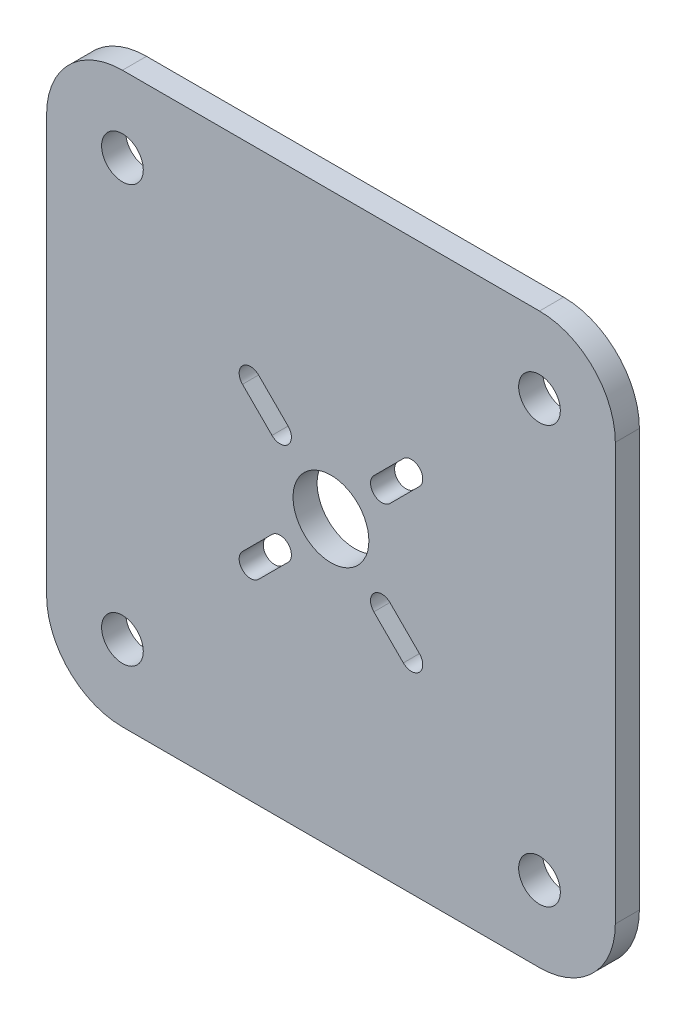
SolidWorks part; units mm, degrees
ref_plane "Front Plane" through (0, 0, 0) normal (0, 0, 1) x (1, 0, 0)
ref_plane "Top Plane" through (0, 0, 0) normal (0, 1, 0) x (1, 0, 0)
ref_plane "Right Plane" through (0, 0, 0) normal (1, 0, 0) x (0, 0, -1)
sketch "Sketch1" plane through (0, 0, 151.125) normal (0, 0, 1) x (1, 0, 0)
  line L1 (-37.5, 241.9) -> (37.5, 241.9)
  line L2 (-37.5, 241.9) -> (-37.5, 316.9)
  line L3 (-37.5, 316.9) -> (37.5, 316.9)
  line L4 (37.5, 241.9) -> (37.5, 316.9)
  line L5 (-37.5, 241.9) -> (37.5, 316.9) construction
  line L6 (-37.5, 316.9) -> (37.5, 241.9) construction
  circle A0 centre (0, 279.4) radius 3.25 construction
  circle A1 centre (-27.5, 251.9) radius 2.75 construction
  circle A2 centre (27.5, 251.9) radius 2.75 construction
  circle A3 centre (27.5, 306.9) radius 2.75 construction
  circle A4 centre (-27.5, 306.9) radius 2.75 construction
  circle A5 centre (0, 279.4) radius 3.25 construction
  circle A6 centre (-27.5, 251.9) radius 2.75
  circle A7 centre (27.5, 251.9) radius 2.75
  circle A8 centre (27.5, 306.9) radius 2.75
  circle A9 centre (-27.5, 306.9) radius 2.75
  circle A10 centre (0, 279.4) radius 5
  dimension "D1" = 10
  dimension "D2" = 75
extrude "Boss-Extrude1" add sketch "Sketch1" along normal blind 3.175
sketch "Sketch2" plane through (0, 0, 154.3) normal (0, 0, 1) x (1, 0, 0)
  line L0 (6.7175, 286.1175) -> (10.6066, 290.0066) construction
  line L1 (-6.7175, 272.6825) -> (6.7175, 272.6825) construction
  line L2 (-6.7175, 272.6825) -> (-6.7175, 286.1175) construction
  line L3 (-6.7175, 286.1175) -> (6.7175, 286.1175) construction
  line L4 (6.7175, 272.6825) -> (6.7175, 286.1175) construction
  line L5 (-6.7175, 272.6825) -> (6.7175, 286.1175) construction
  line L6 (-6.7175, 286.1175) -> (6.7175, 272.6825) construction
  line L7 (5.6569, 287.1782) -> (9.5459, 291.0673)
  line L8 (7.7782, 285.0569) -> (11.6673, 288.9459)
  line L9 (6.7175, 272.6825) -> (10.6066, 268.7934) construction
  line L10 (7.7782, 273.7431) -> (11.6673, 269.8541)
  line L11 (5.6569, 271.6218) -> (9.5459, 267.7327)
  line L12 (-6.7175, 272.6825) -> (-10.6066, 268.7934) construction
  line L13 (-5.6569, 271.6218) -> (-9.5459, 267.7327)
  line L14 (-7.7782, 273.7431) -> (-11.6673, 269.8541)
  line L15 (-6.7175, 286.1175) -> (-10.6066, 290.0066) construction
  line L16 (-7.7782, 285.0569) -> (-11.6673, 288.9459)
  line L17 (-5.6569, 287.1782) -> (-9.5459, 291.0673)
  circle A0 centre (0, 279.4) radius 5 construction
  circle A1 centre (0, 279.4) radius 5 construction
  circle A2 centre (0, 279.4) radius 9.5 construction
  circle A3 centre (0, 279.4) radius 15 construction
  arc A4 (5.6569, 287.1782) -> (7.7782, 285.0569) centre (6.7175, 286.1175) ccw
  arc A5 (11.6673, 288.9459) -> (9.5459, 291.0673) centre (10.6066, 290.0066) ccw
  arc A6 (7.7782, 273.7431) -> (5.6569, 271.6218) centre (6.7175, 272.6825) ccw
  arc A7 (9.5459, 267.7327) -> (11.6673, 269.8541) centre (10.6066, 268.7934) ccw
  arc A8 (-5.6569, 271.6218) -> (-7.7782, 273.7431) centre (-6.7175, 272.6825) ccw
  arc A9 (-11.6673, 269.8541) -> (-9.5459, 267.7327) centre (-10.6066, 268.7934) ccw
  arc A10 (-7.7782, 285.0569) -> (-5.6569, 287.1782) centre (-6.7175, 286.1175) ccw
  arc A11 (-9.5459, 291.0673) -> (-11.6673, 288.9459) centre (-10.6066, 290.0066) ccw
  point P9 (8.6621, 288.0621)
  point P15 (0, 0)
  point P16 (0, 279.4)
  point P19 (8.6621, 270.7379)
  point P26 (-8.6621, 270.7379)
  point P33 (-8.6621, 288.0621)
  point P39 (0, 279.4)
  dimension "D1" = 19
  dimension "D2" = 30
  dimension "D3" = 1.5
  dimension "D4" = 4
extrude "Cut-Extrude1" cut sketch "Sketch2" against normal through all both and the other way through all
fillet "Fillet1" radius 10 4 edges at (-37.5, 316.9, 152.7125) (-37.5, 241.9, 152.7125) (37.5, 241.9, 152.7125) (37.5, 316.9, 152.7125)
